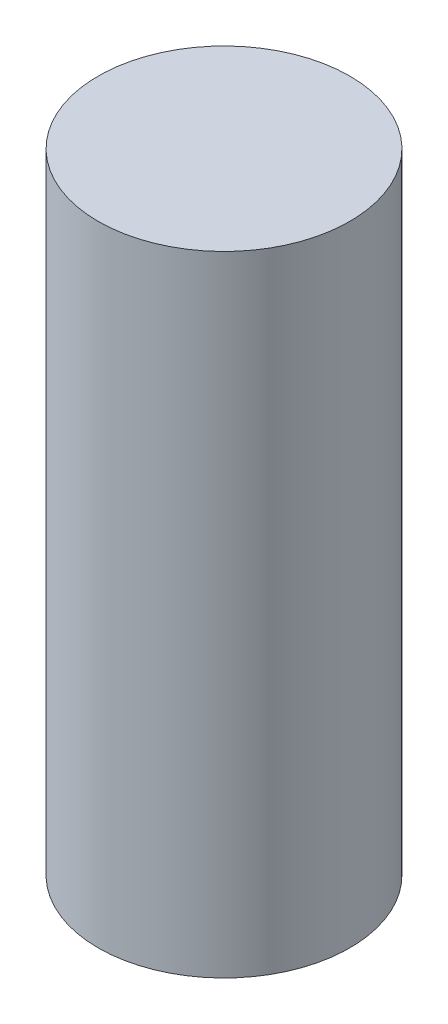
SolidWorks part; units mm, degrees
ref_plane "Front Plane" through (0, 0, 0) normal (0, 0, 1) x (1, 0, 0)
ref_plane "Top Plane" through (0, 0, 0) normal (0, 1, 0) x (1, 0, 0)
ref_plane "Right Plane" through (0, 0, 0) normal (1, 0, 0) x (0, 0, -1)
sketch "Sketch1" plane through (0, 0, 0) normal (0, 1, 0) x (1, 0, 0)
  circle A0 centre (0, 0) radius 3
  dimension "D1" = 6
extrude "Boss-Extrude1" add sketch "Sketch1" along normal blind 15
